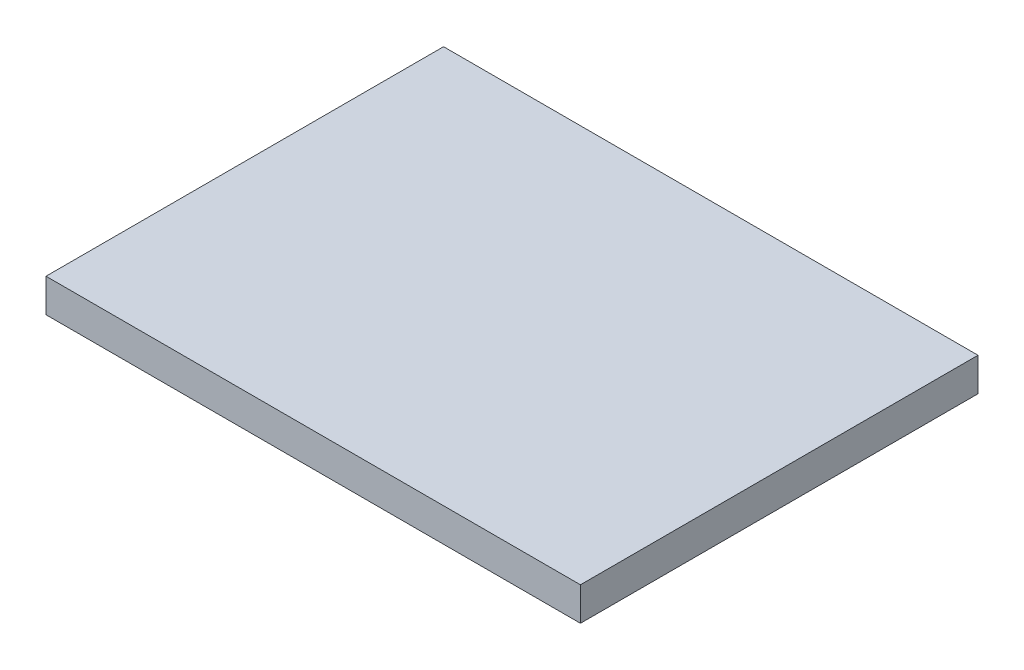
SolidWorks part; units mm, degrees
ref_plane "Front Plane" through (0, 0, 0) normal (0, 0, 1) x (1, 0, 0)
ref_plane "Top Plane" through (0, 0, 0) normal (0, 1, 0) x (1, 0, 0)
ref_plane "Right Plane" through (0, 0, 0) normal (1, 0, 0) x (0, 0, -1)
sketch "Sketch1" plane through (0, 0, 0) normal (0, 1, 0) x (1, 0, 0)
  line L1 (0, 0) -> (101.6895, 0)
  line L2 (0, 0) -> (0, 75.6471)
  line L3 (0, 75.6471) -> (101.6895, 75.6471)
  line L4 (101.6895, 0) -> (101.6895, 75.6471)
extrude "Boss-Extrude1" add sketch "Sketch1" along normal blind 6.35
